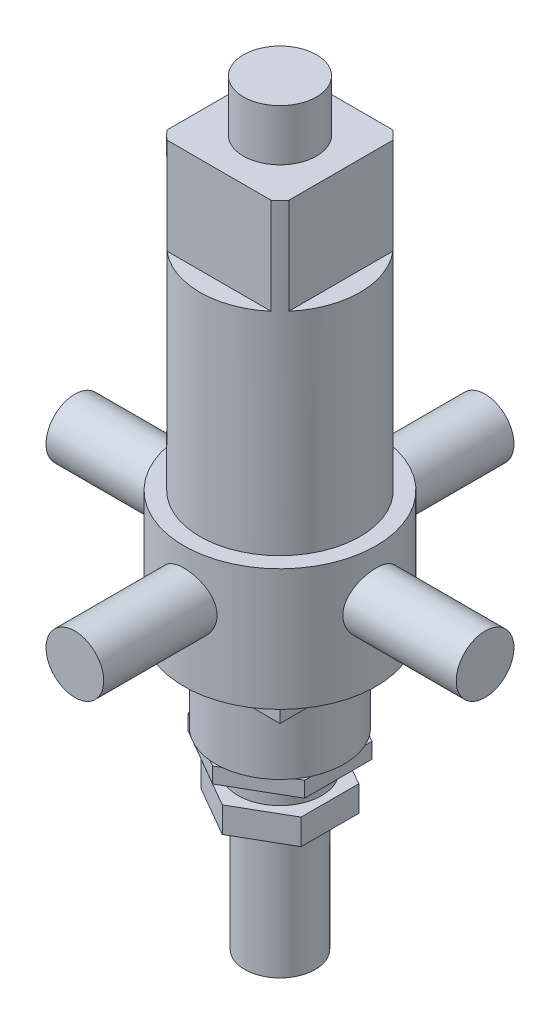
SolidWorks part; units mm, degrees
ref_plane "Спереди" through (0, 0, 0) normal (0, 0, 1) x (1, 0, 0)
ref_plane "Сверху" through (0, 0, 0) normal (0, 1, 0) x (1, 0, 0)
ref_plane "Справа" through (0, 0, 0) normal (1, 0, 0) x (0, 0, -1)
sketch "Эскиз2" plane through (0, 0, 0) normal (0, 0, 1) x (1, 0, 0)
  line L0 (0, 0) -> (0, 110) construction
  line L1 (0, 110) -> (12.5, 110)
  line L2 (12.5, 110) -> (12.5, 62)
  line L3 (12.5, 62) -> (15, 62)
  line L4 (15, 62) -> (15, 40)
  line L5 (15, 40) -> (10, 40)
  line L6 (10, 40) -> (10, 30)
  line L7 (10, 30) -> (10.5, 30)
  line L8 (10.5, 30) -> (10.5, 27.5752)
  line L9 (10.5, 27.5752) -> (6.5083, 27.5752)
  line L10 (6.5083, 27.5752) -> (6.5083, 24)
  line L11 (6.5083, 24) -> (9, 24)
  line L12 (9, 24) -> (9, 20)
  line L13 (9, 20) -> (5.5, 20)
  line L14 (5.5, 20) -> (5.5, 0)
  line L15 (5.5, 0) -> (0, 0)
  line L16 (0, 0) -> (0, 110)
  dimension "D1" = 110
  dimension "D2" = 20
  dimension "D3" = 25
  dimension "D4" = 30
  dimension "D5" = 18
  dimension "D6" = 21
  dimension "D7" = 20
  dimension "D8" = 4
  dimension "D9" = 30
  dimension "D10" = 40
  dimension "D11" = 22
  dimension "D12" = 11
revolve "Повернуть1" add sketch "Эскиз2" angle 360 about L0
sketch "Эскиз3" plane through (0, 110, 0) normal (0, 1, 0) x (1, 0, 0)
  line L1 (9.5, 9.5) -> (-9.5, 9.5)
  line L2 (9.5, 9.5) -> (9.5, -9.5)
  line L3 (9.5, -9.5) -> (-9.5, -9.5)
  line L4 (-9.5, 9.5) -> (-9.5, -9.5)
  line L5 (9.5, 9.5) -> (-9.5, -9.5) construction
  line L6 (9.5, -9.5) -> (-9.5, 9.5) construction
  circle A0 centre (0, 0) radius 14.3473
  point P0 (0, 0)
  dimension "D1" = 19
extrude "Вырез-Вытянуть1" cut sketch "Эскиз3" against normal blind 15
sketch "Эскиз4" plane through (0, 20, 0) normal (0, -1, 0) x (1, 0, 0)
  line L1 (0, 9) -> (-7.7942, 4.5)
  line L2 (-7.7942, 4.5) -> (-7.7942, -4.5)
  line L3 (-7.7942, -4.5) -> (0, -9)
  line L4 (0, -9) -> (7.7942, -4.5)
  line L5 (7.7942, -4.5) -> (7.7942, 4.5)
  line L6 (7.7942, 4.5) -> (0, 9)
  circle A0 centre (0, 0) radius 7.7942 construction
  circle A1 centre (0, 0) radius 9.8084
extrude "Вырез-Вытянуть2" cut sketch "Эскиз4" against normal blind 4
sketch "Эскиз5" plane through (0, 27.5752, 0) normal (0, -1, 0) x (1, 0, 0)
  line L1 (0, 10.5) -> (-9.0933, 5.25)
  line L2 (-9.0933, 5.25) -> (-9.0933, -5.25)
  line L3 (-9.0933, -5.25) -> (0, -10.5)
  line L4 (0, -10.5) -> (9.0933, -5.25)
  line L5 (9.0933, -5.25) -> (9.0933, 5.25)
  line L6 (9.0933, 5.25) -> (0, 10.5)
  circle A0 centre (0, 0) radius 9.0933 construction
  circle A1 centre (0, 0) radius 11.6648
extrude "Вырез-Вытянуть3" cut sketch "Эскиз5" against normal up to surface (2.4248 mm away) up to face at (0, 30, -10)
sketch "Эскиз6" plane through (0, 40, 0) normal (0, -1, 0) x (1, 0, 0)
  line L1 (9.5, -9.5) -> (-9.5, -9.5)
  line L2 (9.5, -9.5) -> (9.5, 9.5)
  line L3 (9.5, 9.5) -> (-9.5, 9.5)
  line L4 (-9.5, -9.5) -> (-9.5, 9.5)
  line L5 (9.5, -9.5) -> (-9.5, 9.5) construction
  line L6 (9.5, 9.5) -> (-9.5, -9.5) construction
  circle A0 centre (0, 0) radius 18.2482
  point P0 (0, 0)
  dimension "D1" = 19
extrude "Вырез-Вытянуть4" cut sketch "Эскиз6" against normal blind 3
ref_plane "Плоскость4" through (0, 0, 15) normal (0, 0, 1) x (1, 0, 0)
sketch "Эскиз8" plane through (0, 0, 15) normal (0, 0, 1) x (1, 0, 0)
  line L0 (0, 0) -> (0, 110) construction
  line L1 (-8.124, 110) -> (8.124, 110) construction
  line L2 (15, 62) -> (-15, 62) construction
  circle A0 centre (0, 54.5) radius 4.5
  point P7 (0, 59)
  dimension "D1" = 9
  dimension "D2" = 3
extrude "Бобышка-Вытянуть1" add sketch "Эскиз8" along normal blind 17 and the other way blind 47 separate body
sketch "Эскиз9" plane through (0, 110, 0) normal (0, 1, 0) x (1, 0, 0)
  circle A0 centre (0, 0) radius 5.7
  dimension "D1" = 11.4
extrude "Бобышка-Вытянуть2" add sketch "Эскиз9" along normal blind 8
sketch "Эскиз10" plane through (0, 0, 0) normal (1, 0, 0) x (0, 0, -1)
  line L0 (-32, 54.5) -> (32, 54.5) construction
  line L1 (-32, 59) -> (-32, 50) construction
  line L2 (32, 50) -> (32, 59) construction
  circle A0 centre (0, 54.5) radius 4.5
  dimension "D1" = 9
extrude "Бобышка-Вытянуть3" add sketch "Эскиз10" along normal blind 32 and the other way blind 32
